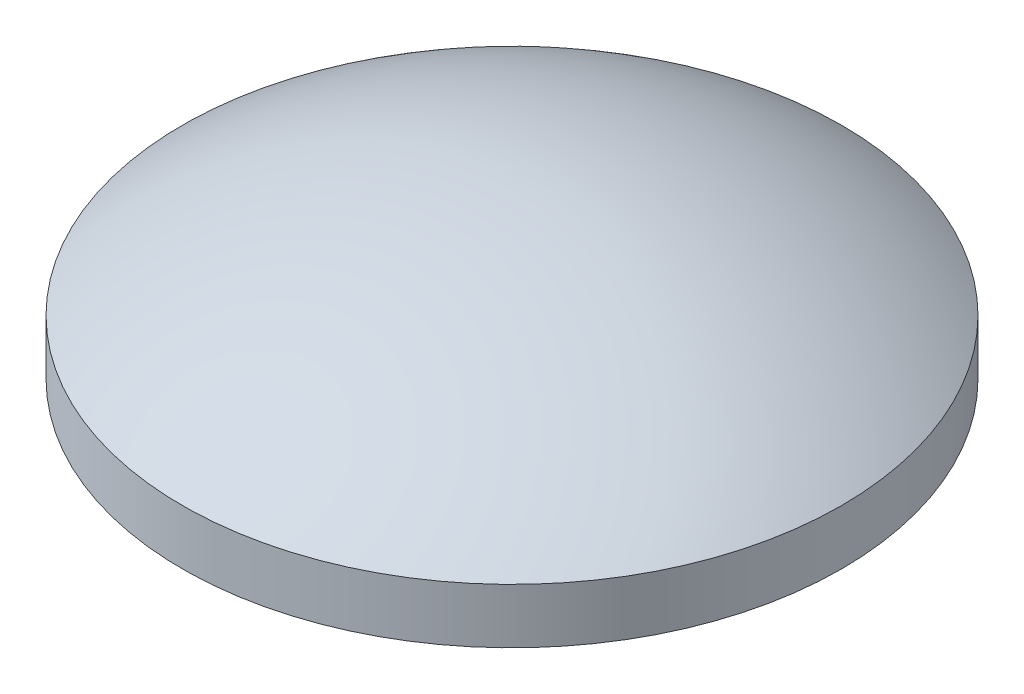
SolidWorks part; units mm, degrees
ref_plane "前视基准面" through (0, 0, 0) normal (0, 0, 1) x (1, 0, 0)
ref_plane "上视基准面" through (0, 0, 0) normal (0, 1, 0) x (1, 0, 0)
ref_plane "右视基准面" through (0, 0, 0) normal (1, 0, 0) x (0, 0, -1)
other "Configuration Table"
sketch "草图1" plane through (0, 0, 0) normal (0, 0, 1) x (1, 0, 0)
  line L0 (0, -0.1645) -> (0, 7.8311) construction
  line L3 (6, 8) -> (6, 7)
  line L4 (0, 10) -> (0, 9)
  arc A0 (0, 10) -> (6, 8) centre (0, 0) cw
  arc A1 (0, 9) -> (6, 7) centre (0, -1) cw
  point P8 (0, 0)
  dimension "D1" = 10
  dimension "D2" = 1
  dimension "D3" = 1
  dimension "6" = 6
revolve "旋转1" add sketch "草图1" angle 360 about L0
